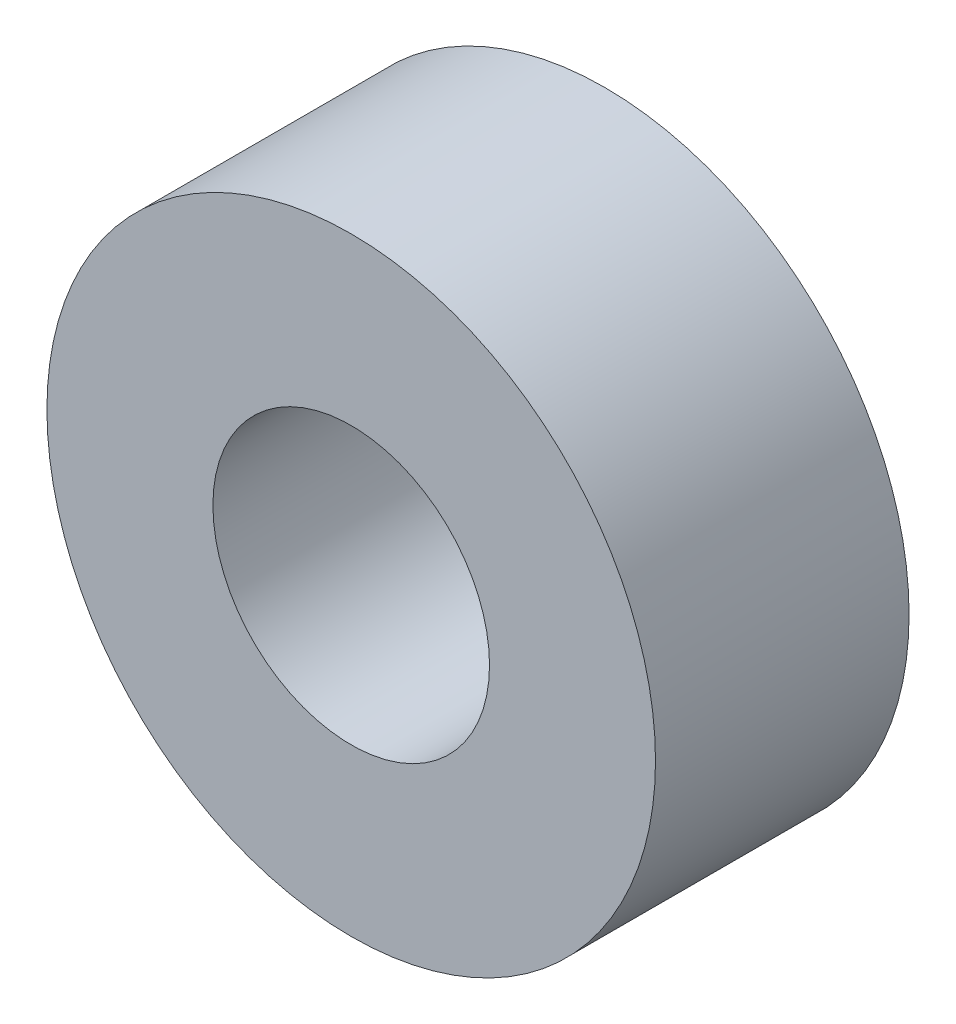
SolidWorks part; units mm, degrees
ref_plane "Front Plane" through (0, 0, 0) normal (0, 0, 1) x (1, 0, 0)
ref_plane "Top Plane" through (0, 0, 0) normal (0, 1, 0) x (1, 0, 0)
ref_plane "Right Plane" through (0, 0, 0) normal (1, 0, 0) x (0, 0, -1)
sketch "Sketch1" plane through (0, 0, 0) normal (0, 0, 1) x (1, 0, 0)
  circle A0 centre (0, 0) radius 1.5
  circle A1 centre (0, 0) radius 3.3
  dimension "D1" = 6.6
  dimension "D2" = 3
extrude "Boss-Extrude1" add sketch "Sketch1" along normal mid plane 2.75
